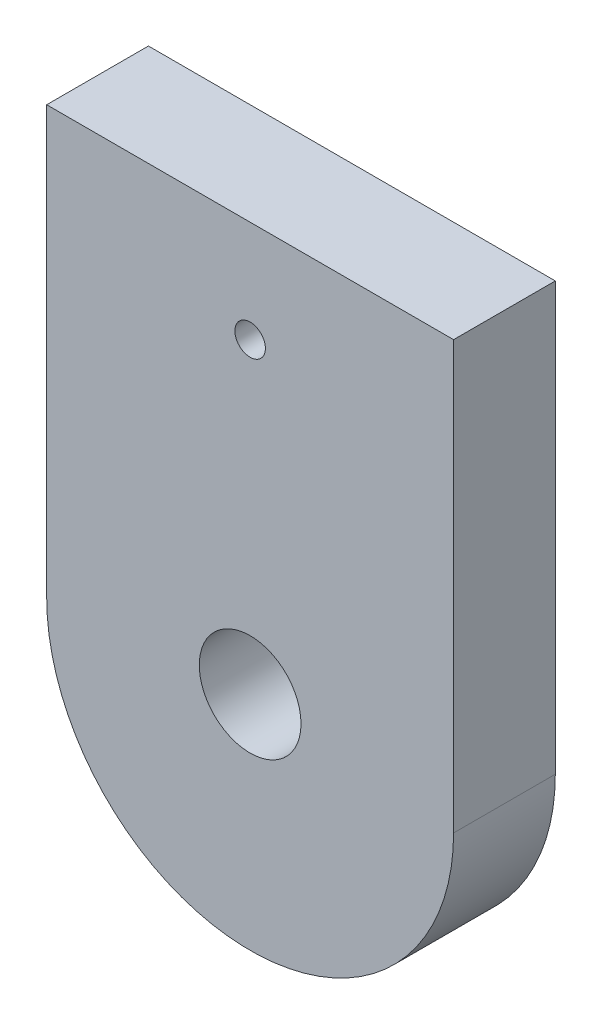
SolidWorks part; units mm, degrees
ref_plane "Front Plane" through (0, 0, 0) normal (0, 0, 1) x (1, 0, 0)
ref_plane "Top Plane" through (0, 0, 0) normal (0, 1, 0) x (1, 0, 0)
ref_plane "Right Plane" through (0, 0, 0) normal (1, 0, 0) x (0, 0, -1)
sketch "Sketch1" plane through (0, 0, 0) normal (0, 0, 1) x (1, 0, 0)
  line L0 (0, 78.0535) -> (0, -76.7078) construction
  line L1 (-108.1983, 0.6729) -> (119.7718, 0.6729) construction
  line L2 (-12.0732, -76.7078) -> (17.2347, -76.7078) construction
  line L3 (-20, -76.7078) -> (-20, -58.5041)
  line L4 (-20, -34.7078) -> (20, -34.7078)
  line L5 (20, -34.7078) -> (20, -76.7078)
  line L6 (-20, -34.7078) -> (-120, -33.5041)
  line L7 (-120, -33.5041) -> (-120, -58.5041)
  line L8 (-120, -58.5041) -> (-20, -58.5041)
  arc A0 (-20, -76.7078) -> (20, -76.7078) centre (0, -76.7078) ccw
  circle A1 centre (0, -44.7078) radius 1.5
  circle A2 centre (-100, -43.7456) radius 1.5
  dimension "D1" = 40
  dimension "D10" = 3
  dimension "D11" = 3
  dimension "D2" = 40
  dimension "D3" = 42
  dimension "D4" = 100
  dimension "D5" = 25
  dimension "D6" = 100
  dimension "D7" = 10
  dimension "D8" = 10
  dimension "D9" = 20
extrude "Boss-Extrude1" add sketch "Sketch1" along normal blind 10
sketch "Sketch2" plane through (0, 0, 10) normal (0, 0, 1) x (1, 0, 0)
  line L0 (0, -39.6329) -> (0, -110.1829) construction
  line L1 (-29.4048, -74.9079) -> (47.7155, -74.9079) construction
  circle A0 centre (0, -74.9079) radius 5
extrude "Cut-Extrude1" cut sketch "Sketch2" against normal blind 24 and the other way blind 37
sketch "Sketch3" plane through (0, 0, 0) normal (0, 0, 1) x (1, 0, 0)
  line L0 (-20, -21.3501) -> (-20, -106.6141) construction
  line L2 (-122.6767, -28.6927) -> (-20, -28.6927)
  line L3 (-122.6767, -28.6927) -> (-122.6767, -71.6993)
  line L4 (-122.6767, -71.6993) -> (-20, -71.6993)
  line L5 (-20, -28.6927) -> (-20, -71.6993)
extrude "Cut-Extrude2" cut sketch "Sketch3" against normal blind 19 and the other way blind 27
